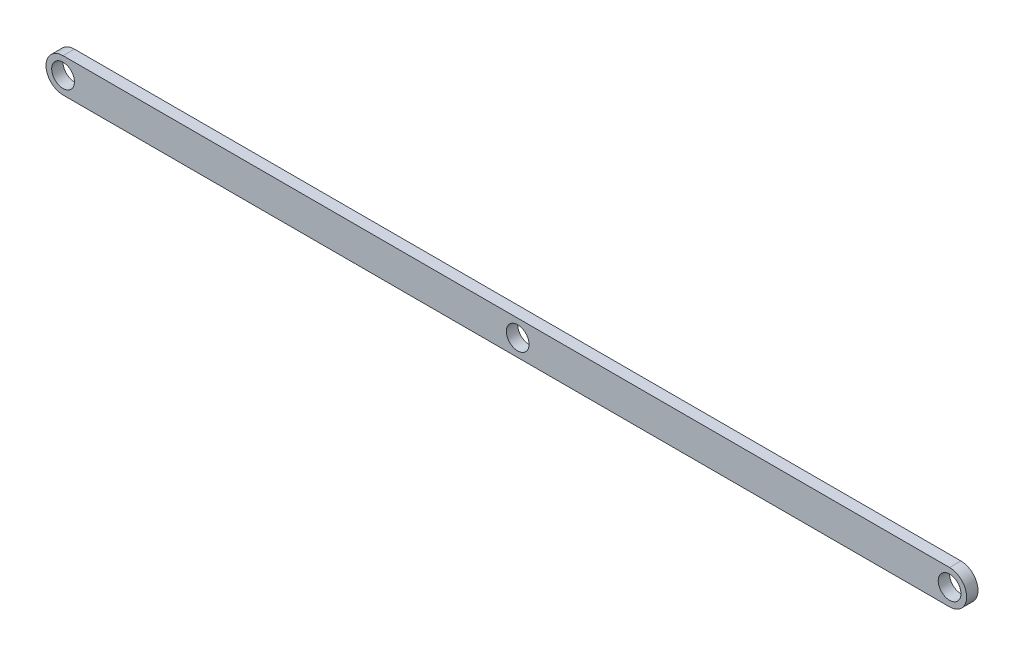
SolidWorks part; units mm, degrees
ref_plane "Спереди" through (0, 0, 0) normal (0, 0, 1) x (1, 0, 0)
ref_plane "Сверху" through (0, 0, 0) normal (0, 1, 0) x (1, 0, 0)
ref_plane "Справа" through (0, 0, 0) normal (1, 0, 0) x (0, 0, -1)
other "Configuration Table"
sketch "Эскиз1" plane through (0, 0, 0) normal (0, 0, 1) x (1, 0, 0)
  line L0 (0, 0) -> (780, 0) construction
  line L1 (0, 15) -> (780, 15)
  line L2 (0, -15) -> (780, -15)
  line L3 (0, 0) -> (0, -137.0331) construction
  line L4 (400, -1000) -> (400, 49000) construction
  arc A0 (0, 15) -> (0, -15) centre (0, 0) ccw
  arc A1 (780, -15) -> (780, 15) centre (780, 0) ccw
  circle A2 centre (0, 0) radius 10
  circle A3 centre (780, 0) radius 10
  circle A4 centre (400, 0) radius 10
  point P3 (390, 0)
  point P13 (400, 0)
  dimension "D3" = 400
  dimension "D1" = 780
  dimension "D2" = 30
extrude "Бобышка-Вытянуть2" add sketch "Эскиз1" along normal blind 10
